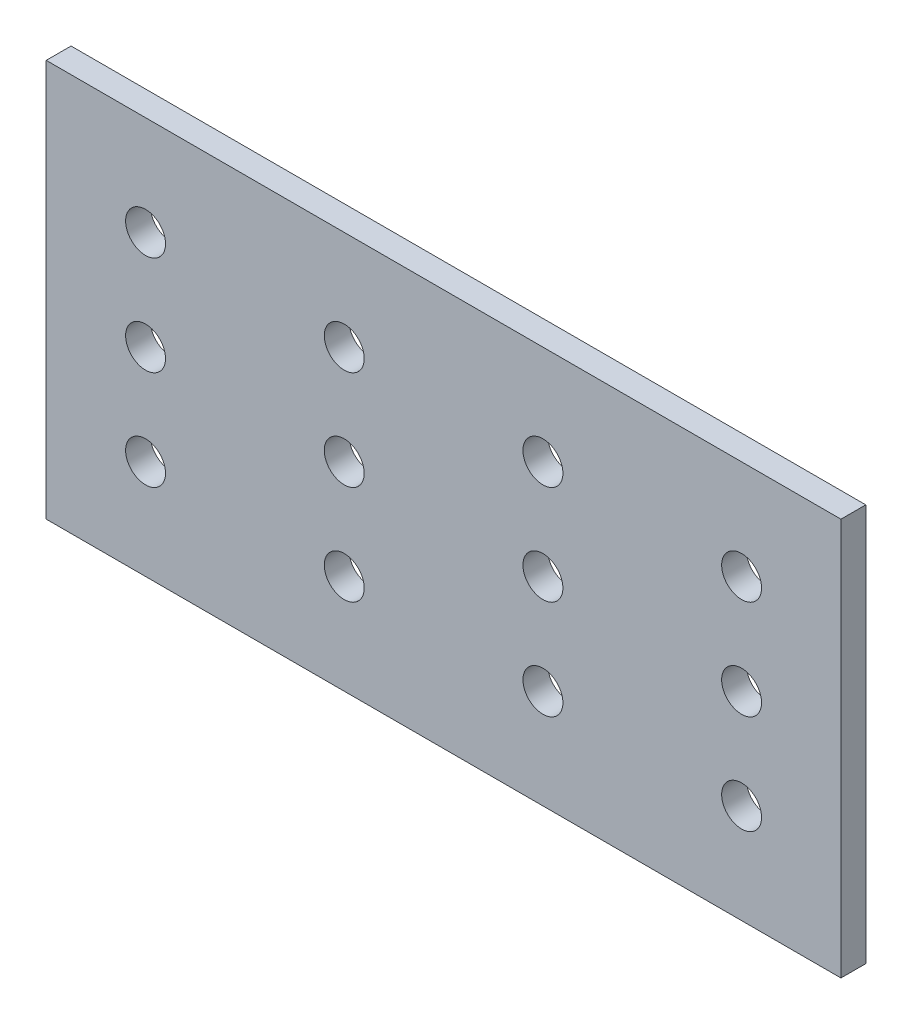
SolidWorks part; units mm, degrees
material "6061 Alloy"
ref_plane "Front Plane" through (0, 0, 0) normal (0, 0, 1) x (1, 0, 0)
ref_plane "Top Plane" through (0, 0, 0) normal (0, 1, 0) x (1, 0, 0)
ref_plane "Right Plane" through (0, 0, 0) normal (1, 0, 0) x (0, 0, -1)
sketch "Sketch1" plane through (0, 0, 0) normal (0, 0, 1) x (1, 0, 0)
  line L1 (-50.8, 25.4) -> (50.8, 25.4)
  line L2 (-50.8, 25.4) -> (-50.8, -25.4)
  line L3 (-50.8, -25.4) -> (50.8, -25.4)
  line L4 (50.8, 25.4) -> (50.8, -25.4)
  dimension "D1" = 101.6
  dimension "D2" = 50.8
  dimension "D3" = 25.4
  dimension "D4" = 50.8
extrude "Boss-Extrude1" add sketch "Sketch1" along normal blind 3.175
sketch "Sketch2" plane through (0, 0, 3.175) normal (0, 0, 1) x (1, 0, 0)
  line L0 (50.8, 25.4) -> (-50.8, 25.4) construction
  line L1 (-50.8, 25.4) -> (-50.8, -25.4) construction
  circle A0 centre (-38.1, 12.7) radius 2.5527
  circle A1 centre (-12.7, 12.7) radius 2.5527
  circle A2 centre (12.7, 12.7) radius 2.5527
  circle A3 centre (38.1, 12.7) radius 2.5527
  circle A4 centre (-12.7, 0) radius 2.5527
  circle A5 centre (12.7, 0) radius 2.5527
  circle A6 centre (38.1, 0) radius 2.5527
  circle A7 centre (-12.7, -12.7) radius 2.5527
  circle A8 centre (12.7, -12.7) radius 2.5527
  circle A9 centre (38.1, -12.7) radius 2.5527
  circle A10 centre (-38.1, 0) radius 2.5527
  circle A11 centre (-38.1, -12.7) radius 2.5527
  dimension "D1" = 5.1054
  dimension "D2" = 12.7
  dimension "D3" = 12.7
  dimension "D4" = 4
  dimension "D5" = 3
extrude "Cut-Extrude1" cut sketch "Sketch2" against normal through all
